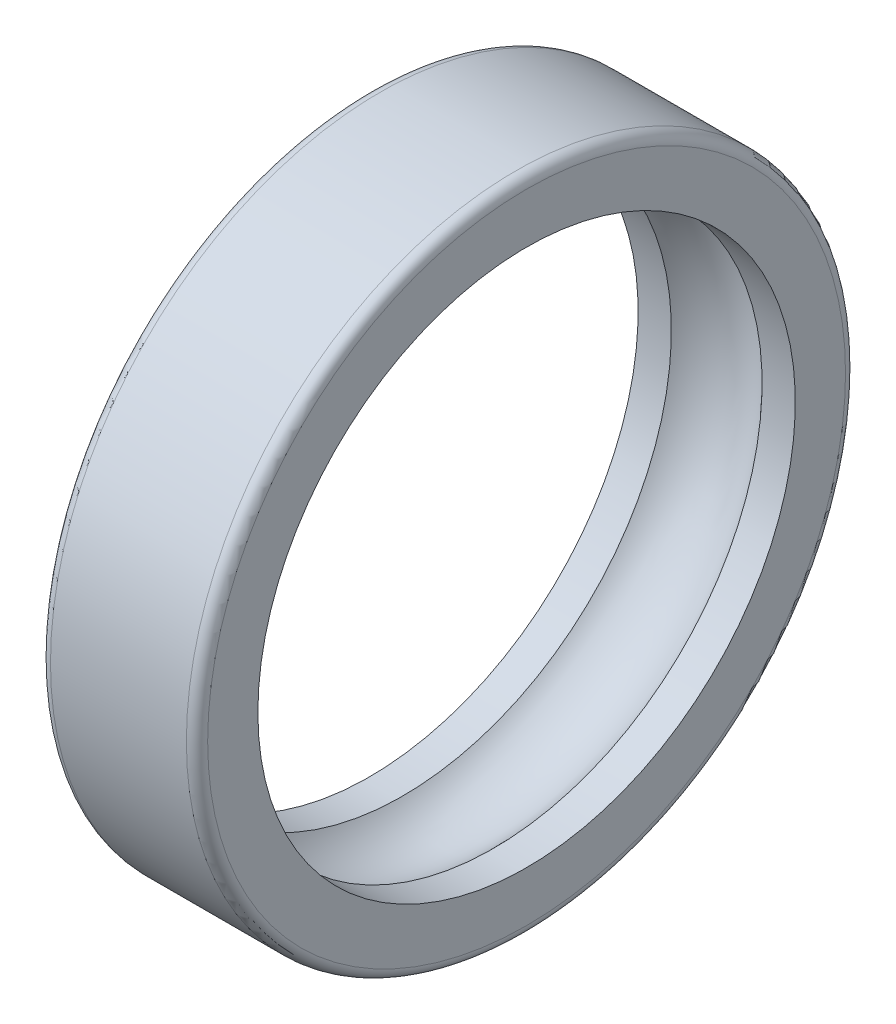
SolidWorks part; units mm, degrees
ref_plane "Спереди" through (0, 0, 0) normal (0, 0, 1) x (1, 0, 0)
ref_plane "Сверху" through (0, 0, 0) normal (0, 1, 0) x (1, 0, 0)
ref_plane "Справа" through (0, 0, 0) normal (1, 0, 0) x (0, 0, -1)
sketch "Sketch1" plane through (0, 0, 0) normal (0, 0, 1) x (1, 0, 0)
  line L0 (-18.2884, 0) -> (29.5238, 0) construction
  line L1 (0, 53) -> (0, 0) construction
  line L2 (15.5, 53) -> (8.9443, 53)
  line L3 (15.5, 53) -> (15.5, 65)
  line L4 (15.5, 65) -> (-15.5, 65)
  line L5 (-15.5, 53) -> (-15.5, 65)
  line L6 (15.5, 53) -> (-15.5, 65) construction
  line L7 (15.5, 65) -> (-15.5, 53) construction
  line L8 (-8.9443, 53) -> (-15.5, 53)
  arc A0 (-8.9443, 53) -> (8.9443, 53) centre (0, 45) cw
  point P3 (0, 59)
  dimension "D5" = 12
  dimension "D1" = 31
  dimension "D2" = 53
  dimension "D3" = 65
  dimension "D4" = 8
revolve "Revolve1" add sketch "Sketch1" angle 360 about L0
fillet "Fillet1" radius 2.1 2 edges at (15.5, 0, 65) (-15.5, 0, 65)
